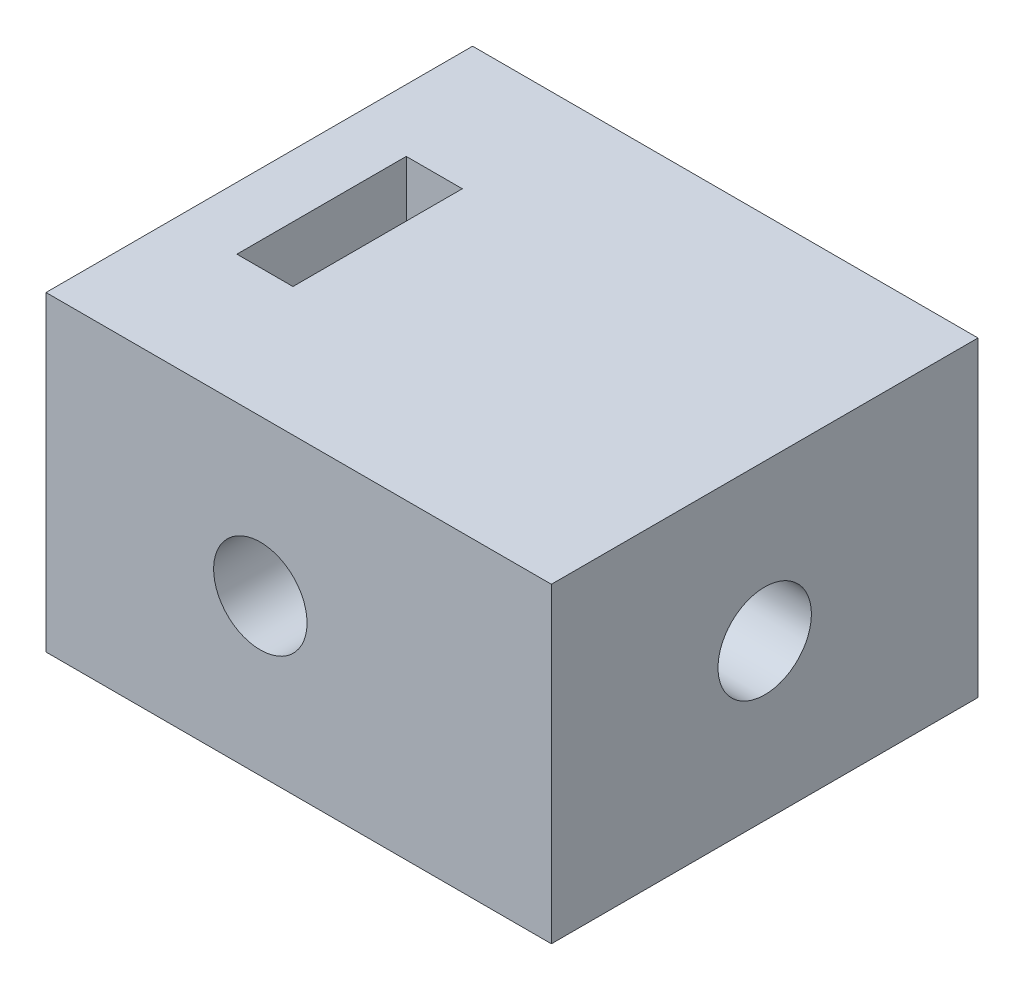
SolidWorks part; units mm, degrees
ref_plane "Front Plane" through (0, 0, 0) normal (0, 0, 1) x (1, 0, 0)
ref_plane "Top Plane" through (0, 0, 0) normal (0, 1, 0) x (1, 0, 0)
ref_plane "Right Plane" through (0, 0, 0) normal (1, 0, 0) x (0, 0, -1)
sketch "Sketch2" plane through (0, 0, 0) normal (0, 0, 1) x (1, 0, 0)
  line B0 (0, 10) -> (16.23, 10)
  line B1 (0, 10) -> (0, 0)
  line B2 (0, 0) -> (16.23, 0)
  line B3 (16.23, 10) -> (16.23, 0)
  circle B4 centre (6.8829, 5) radius 1.5
sketch_block_instance "Block-BracketBlockMiddleSketch-1"
sketch_block "Block1" parameters "D1"=10, "D2"=16.23
extrude "Boss-Extrude1" add sketch "Sketch2" along normal blind 13.7
sketch "Sketch3" plane through (16.23, 0, 0) normal (1, 0, 0) x (0, 0, -1)
  line L0 (-13.7, 10) -> (0, 10) construction
  line L1 (-13.7, 10) -> (0, 10) construction
  line L2 (-13.7, 10) -> (-13.7, 0) construction
  line L3 (-13.7, 0) -> (0, 0) construction
  line L4 (0, 10) -> (0, 0) construction
  line L5 (-13.7, 10) -> (0, 0) construction
  line L6 (-13.7, 0) -> (0, 10) construction
  line L7 (-13.7, 0) -> (-13.7, 10) construction
  circle A0 centre (-6.85, 5) radius 1.5
  point P0 (-6.85, 5)
  dimension "D1" = 3
extrude "Cut-Extrude1" cut sketch "Sketch3" against normal through all
ref_plane "Plane2" through (0, 0, 6.85) normal (0, 0, 1) x (1, 0, 0)
ref_plane "Plane3" through (2, 0, 0) normal (-1, 0, 0) x (0, 0, 1)
sketch "Sketch4" plane through (2, 0, 0) normal (1, 0, 0) x (0, 0, -1)
  line L1 (-5.4903, 2.645) -> (-4.1307, 5)
  line L2 (-4.1307, 5) -> (-5.4903, 7.355)
  line L3 (-5.4903, 7.355) -> (-8.2097, 7.355)
  line L4 (-8.2097, 7.355) -> (-9.5693, 5)
  line L5 (-9.5693, 5) -> (-8.2097, 2.645)
  line L6 (-8.2097, 2.645) -> (-5.4903, 2.645)
  circle A0 centre (-6.85, 5) radius 2.355 construction
  dimension "D1" = 4.71
extrude "Cut-Extrude4" cut sketch "Sketch4" along normal blind 1.8
sketch "Sketch7" plane through (0, 10, 0) normal (0, 1, 0) x (1, 0, 0)
  line L0 (2, -4.1307) -> (2, -9.5693)
  line L1 (2, -9.5693) -> (3.8, -9.5693)
  line L2 (3.8, -9.5693) -> (3.8, -4.1307)
  line L3 (3.8, -4.1307) -> (2, -4.1307)
  point P0 (2, -4.1307)
  point P2 (2, -9.5693)
  dimension "D1" = 1.8
extrude "Cut-Extrude5" cut sketch "Sketch7" against normal up to vertex (5 mm away) up to point (2, 5, 9.5693)
sketch "Sketch8" plane through (0, 2.645, 0) normal (0, 1, 0) x (1, 0, 0)
  line L1 (2, -5.4903) -> (3.8, -5.4903)
  line L2 (2, -5.4903) -> (2, -8.2097)
  line L3 (2, -8.2097) -> (3.8, -8.2097)
  line L4 (3.8, -5.4903) -> (3.8, -8.2097)
extrude "Cut-Extrude6" cut sketch "Sketch8" against normal through all
